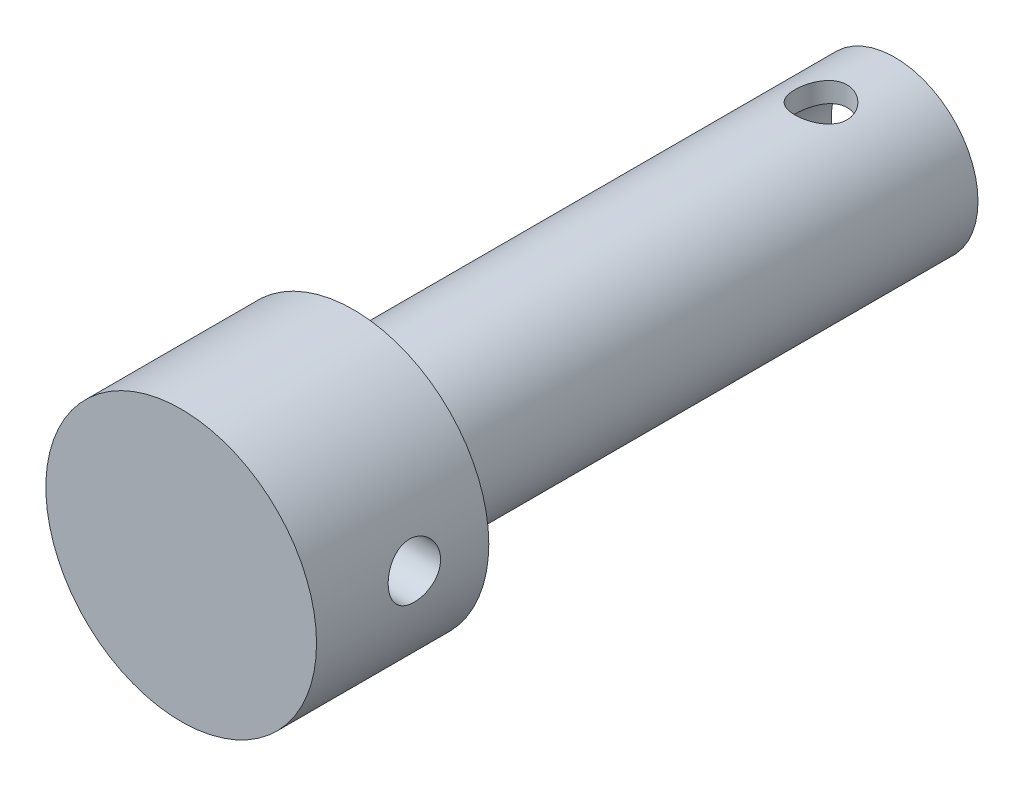
SolidWorks part; units mm, degrees
ref_plane "Front" through (0, 0, 0) normal (0, 0, 1) x (1, 0, 0)
ref_plane "Top" through (0, 0, 0) normal (0, 1, 0) x (1, 0, 0)
ref_plane "Right" through (0, 0, 0) normal (1, 0, 0) x (0, 0, -1)
sketch "Sketch1" plane through (0, 0, 0) normal (0, 0, 1) x (1, 0, 0)
  circle A0 centre (0, 0) radius 10.7315
  circle A1 centre (0, 0) radius 8.1915
  dimension "D1" = 21.463
  dimension "D2" = 16.383
extrude "Boss-Extrude1" add sketch "Sketch1" along normal blind 88.9
sketch "Sketch4" plane through (0, 0, 88.9) normal (0, 0, 1) x (1, 0, 0)
  circle A0 centre (0, 0) radius 17.4625
extrude "Boss-Extrude2" add sketch "Sketch4" against normal blind 19.05
sketch "Sketch5" plane through (0, 0, 0) normal (1, 0, 0) x (0, 0, -1)
  line L1 (-88.9, 17.4625) -> (-88.9, -17.4625) construction
  line L2 (-69.85, 17.4625) -> (-88.9, 17.4625) construction
  circle A0 centre (-79.375, 1.5875) radius 3.3655
  dimension "D1" = 6.731
  dimension "D2" = 9.525
  dimension "D3" = 15.875
extrude "Cut-Extrude1" cut sketch "Sketch5" against normal through all both and the other way through all
sketch "Sketch7" plane through (0, 0, 0) normal (0, 1, 0) x (1, 0, 0)
  line L1 (8.1915, 0) -> (-8.1915, 0) construction
  line L3 (10.7315, 0) -> (-10.7315, 0) construction
  circle A0 centre (0, -9.525) radius 3.3655
  dimension "D1" = 9.525
  dimension "D2" = 9.525
  dimension "D3" = 9.525
  dimension "D4" = 9.525
extrude "Cut-Extrude2" cut sketch "Sketch7" against normal through all both and the other way through all
sketch "Sketch8" plane through (0, 0, 88.9) normal (0, 0, 1) x (1, 0, 0)
  circle A0 centre (0, 0) radius 8.1915
  dimension "D1" = 16.383
extrude "Cut-Extrude3" cut sketch "Sketch8" against normal through all
sketch "Sketch9" plane through (0, 0, 88.9) normal (0, 0, 1) x (1, 0, 0)
  circle A0 centre (0, 0) radius 17.4625
extrude "Boss-Extrude3" add sketch "Sketch9" along normal blind 3.175
